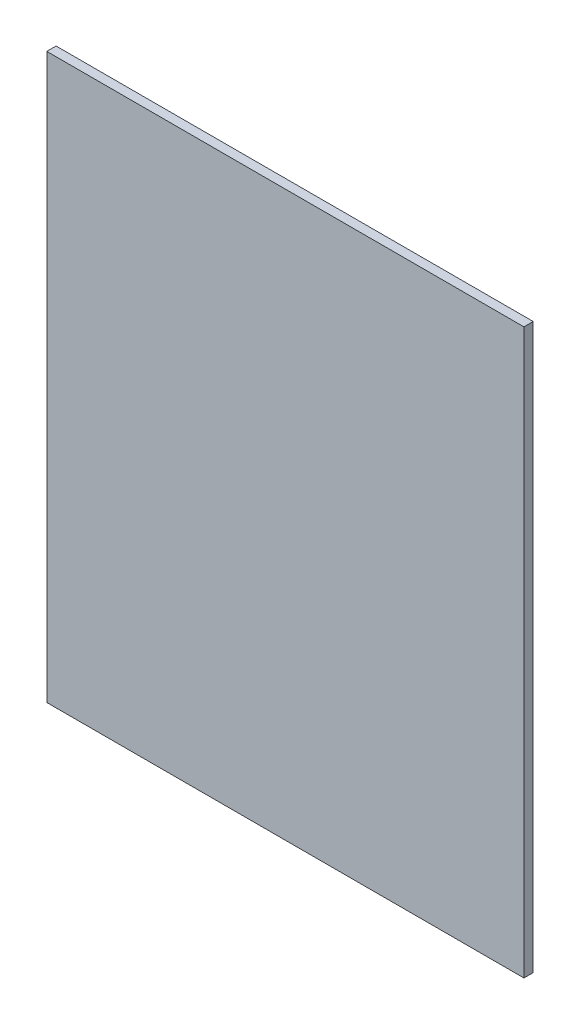
SolidWorks part; units mm, degrees
ref_plane "前视基准面" through (0, 0, 0) normal (0, 0, 1) x (1, 0, 0)
ref_plane "上视基准面" through (0, 0, 0) normal (0, 1, 0) x (1, 0, 0)
ref_plane "右视基准面" through (0, 0, 0) normal (1, 0, 0) x (0, 0, -1)
other "Configuration Table"
sketch "草图1" plane through (0, 0, 0) normal (0, 0, 1) x (1, 0, 0)
  line L1 (0, 0) -> (77, 0)
  line L2 (0, 0) -> (0, -91)
  line L3 (0, -91) -> (77, -91)
  line L4 (77, 0) -> (77, -91)
extrude "凸台-拉伸1" add sketch "草图1" along normal blind 1.5
